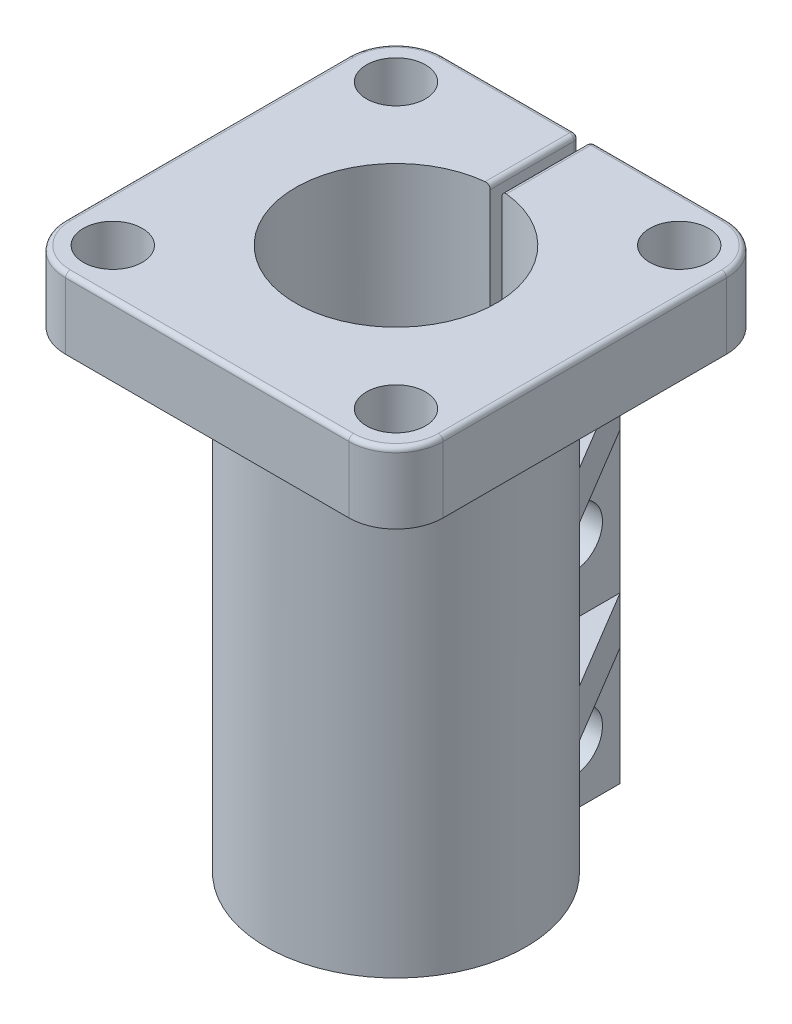
SolidWorks part; units mm, degrees
ref_plane "前视基准面" through (0, 0, 0) normal (0, 0, 1) x (1, 0, 0)
ref_plane "上视基准面" through (0, 0, 0) normal (0, 1, 0) x (1, 0, 0)
ref_plane "右视基准面" through (0, 0, 0) normal (1, 0, 0) x (0, 0, -1)
sketch "草图1" plane through (0, 0, 0) normal (0, 1, 0) x (1, 0, 0)
  line L0 (0, 0) -> (0, 9.0799) construction
  line L1 (-0.25, 8) -> (-0.25, 4.2426)
  line L2 (-0.25, 8) -> (-1.5, 8)
  line L3 (-1.5, 8) -> (-1.5, 5.2915)
  line L4 (1.5, 8) -> (1.5, 5.2915)
  line L5 (0.25, 8) -> (1.5, 8)
  line L6 (0.25, 8) -> (0.25, 4.2426)
  arc A0 (-0.25, 4.2426) -> (0.25, 4.2426) centre (0, 0) ccw
  arc A1 (-1.5, 5.2915) -> (1.5, 5.2915) centre (0, 0) ccw
  dimension "D1" = 8.5
  dimension "D2" = 11
  dimension "D3" = 1.25
  dimension "D4" = 0.25
  dimension "D5" = 8
extrude "凸台-拉伸1" add sketch "草图1" along normal blind 20
sketch "草图2" plane through (0, 20, 0) normal (0, 1, 0) x (1, 0, 0)
  line L0 (0, 0) -> (0, 13.3346) construction
  line L1 (-8, 8) -> (8, 8)
  line L2 (-8, 8) -> (-8, -8)
  line L3 (-8, -8) -> (8, -8)
  line L4 (8, 8) -> (8, -8)
  line L5 (0, 0) -> (13.1784, 0) construction
  dimension "D1" = 16
  dimension "D2" = 16
extrude "凸台-拉伸2" add sketch "草图2" along normal blind 3
sketch "草图3" plane through (0, 0, 0) normal (0, -1, 0) x (1, 0, 0)
  line L2 (0.25, -8) -> (0.25, -4.2426) construction
  line L5 (-0.25, -4.2426) -> (-0.25, -8) construction
  line L6 (-0.25, -8) -> (0.25, -8)
  line L8 (0.25, -8) -> (0.25, -4.2426)
  line L11 (-0.25, -4.2426) -> (-0.25, -8)
  arc A0 (0.25, -4.2426) -> (-0.25, -4.2426) centre (0, 0) ccw construction
  arc A2 (0.25, -4.2426) -> (-0.25, -4.2426) centre (0, 0) ccw
extrude "切除-拉伸1" cut sketch "草图3" against normal through all
sketch "草图4" plane through (0, 0, 0) normal (0, 0, 1) x (1, 0, 0)
  line L0 (-8, 20) -> (-5.5, 17.5)
  line L1 (-5.5, 20) -> (-5.5, 0) construction
rib "筋1" sketch "草图4" sketch "草图4" thickness 2 extrusion direction parallel to sketch draft on no parameters "D1"=2
pattern_circular "阵列(圆周)1" count 4 over 360 about axis through (0, 0, 0) along (0, 1, 0) skipping 3 of "筋1"
ref_plane "基准面1" through (0, 5, 0) normal (0, 1, 0) x (1, 0, 0)
sketch "草图6" plane through (0, 5, 0) normal (0, 1, 0) x (1, 0, 0)
  line L0 (-1.5, 8) -> (-4.0664, 3.7033)
  line L1 (-1.5, 8) -> (-1.5, 5.2915) construction
  line L2 (-1.5, 8) -> (-1.5, 5.2915)
  arc A0 (-1.5, 5.2915) -> (-5.4083, 1) centre (0, 0) ccw construction
  arc A1 (-1.5, 5.2915) -> (-4.0664, 3.7033) centre (0, 0) ccw
extrude "凸台-拉伸3" add sketch "草图6" along normal blind 2
pattern_linear "阵列(线性)1" count 2 spacing 8 along (0, 1, 0) of "凸台-拉伸3"
mirror "镜向1" about plane through (0, 0, 0) normal (1, 0, 0) of "凸台-拉伸3", "阵列(线性)1"
fillet "圆角1" radius 2 4 edges at (8, 21.5, -8) (8, 21.5, 8) (-8, 21.5, 8) (-8, 21.5, -8)
fillet "圆角2" radius 0.2 2 edges at (0.25, 11.5, -8) (-0.25, 11.5, -8)
fillet "圆角4" radius 0.2 13 edges at (0.3086, 23, -7.9414) (3.225, 23, -8) (7.4142, 23, -7.4142) (8, 23, 0) (7.4142, 23, 7.4142) (0, 23, 8) (-7.4142, 23, 7.4142) (-8, 23, 0) (-7.4142, 23, -7.4142) (-3.225, 23, -8) (-0.3086, 23, -7.9414) (0.25, 23, -6.0213) (-0.25, 23, -6.0213)
hole_wizard "M3 螺纹孔的螺纹孔钻头1" positions "草图7" profile "草图8" hole size "M3" standard "GB" end condition up to next
sketch "草图7" plane through (0, 20, 0) normal (0, -1, 0) x (-1, 0, 0)
  line L0 (0, 0) -> (0, 14.1408) construction
  line L2 (0, 0) -> (-17.2024, 0) construction
  arc A0 (7.8, 6) -> (6, 7.8) centre (6, 6) ccw construction
  point P0 (6, 6)
  point P2 (6, -6)
  point P4 (-6, 6)
  point P6 (-6, -6)
sketch "草图8" plane through (-6, 20, -6) normal (1, 0, 0) x (0, 0, -1)
  line L0 (0, 0) -> (0, 3)
  line L1 (0, 3) -> (1.25, 3)
  line L2 (1.25, 3) -> (1.25, 0)
  line L5 (1.25, 0) -> (0, 0)
  line L11 (0, -6.35) -> (0, 107.95) construction
  dimension "通孔孔直径" = 2.5
  dimension "通孔孔深度" = 3
sketch "草图11" plane through (-1.5, 0, 0) normal (-1, 0, 0) x (0, 0, 1)
  line L0 (-9.7616, 17.5) -> (-3.8678, 17.5) construction
  line L1 (-11.8183, 10) -> (-3.1618, 10) construction
  line L2 (-11.3579, 2.5) -> (-3.8678, 2.5) construction
  line L3 (-8, 0) -> (-5.2915, 0) construction
  line L7 (-5.2915, 7) -> (-8, 7) construction
  line L9 (-5.2915, 15) -> (-8, 15) construction
  line L11 (-8, 20) -> (-8, 15) construction
  circle A0 centre (-6, 17.5) radius 1.25
  circle A1 centre (-6, 10) radius 1.25
  circle A2 centre (-6, 2.5) radius 1.25
  dimension "D1" = 2.5
  dimension "D2" = 2.5
  dimension "D3" = 3
  dimension "D4" = 2.5
  dimension "D5" = 2
extrude "切除-拉伸2" cut sketch "草图11" against normal through all and the other way through all
sketch "草图12" plane through (-1.5, 0, 0) normal (-1, 0, 0) x (0, 0, 1)
  circle A0 centre (-6, 17.5) radius 1.75
  circle A1 centre (-6, 10) radius 1.75
  circle A2 centre (-6, 2.5) radius 1.75
  dimension "D1" = 3.5
extrude "切除-拉伸3" cut sketch "草图12" along normal blind 2
sketch "草图13" plane through (1.5, 0, 0) normal (1, 0, 0) x (0, 0, -1)
  line L1 (6, 19.5207) -> (4.25, 18.5104)
  line L2 (4.25, 18.5104) -> (4.25, 16.4896)
  line L3 (4.25, 16.4896) -> (6, 15.4793)
  line L4 (6, 15.4793) -> (7.75, 16.4896)
  line L5 (7.75, 16.4896) -> (7.75, 18.5104)
  line L6 (7.75, 18.5104) -> (6, 19.5207)
  line L7 (6, 12.0207) -> (4.25, 11.0104)
  line L8 (4.25, 11.0104) -> (4.25, 8.9896)
  line L9 (4.25, 8.9896) -> (6, 7.9793)
  line L10 (6, 7.9793) -> (7.75, 8.9896)
  line L11 (7.75, 8.9896) -> (7.75, 11.0104)
  line L12 (7.75, 11.0104) -> (6, 12.0207)
  line L13 (6, 4.5207) -> (4.25, 3.5104)
  line L14 (4.25, 3.5104) -> (4.25, 1.4896)
  line L15 (4.25, 1.4896) -> (6, 0.4793)
  line L16 (6, 0.4793) -> (7.75, 1.4896)
  line L17 (7.75, 1.4896) -> (7.75, 3.5104)
  line L18 (7.75, 3.5104) -> (6, 4.5207)
  circle A0 centre (6, 17.5) radius 1.75 construction
  circle A1 centre (6, 10) radius 1.75 construction
  circle A2 centre (6, 2.5) radius 1.75 construction
  dimension "D1" = 3.5
extrude "切除-拉伸4" cut sketch "草图13" along normal blind 2
sketch "草图16" plane through (0, 0, 8) normal (0, 0, 1) x (1, 0, 0)
  line L0 (0, 0) -> (0, 21.0314) construction
  line L1 (-3.8, 19) -> (-1.7, 19)
  line L2 (-4, 18.8) -> (-4, 17.7)
  line L3 (-3.8, 17.5) -> (-1.7, 17.5)
  line L4 (-1.5, 18.8) -> (-1.5, 17.7)
  line L5 (-5.5, 0) -> (5.5, 0) construction
  line L6 (-6, 20) -> (-1, 20) construction
  line L7 (1.5, 18.8) -> (1.5, 17.7)
  line L8 (3.8, 17.5) -> (1.7, 17.5)
  line L9 (4, 18.8) -> (4, 17.7)
  line L10 (3.8, 19) -> (1.7, 19)
  arc A0 (4, 18.8) -> (3.8, 19) centre (3.8, 18.8) ccw
  arc A1 (3.8, 17.5) -> (4, 17.7) centre (3.8, 17.7) ccw
  arc A2 (1.5, 17.7) -> (1.7, 17.5) centre (1.7, 17.7) ccw
  arc A3 (1.5, 18.8) -> (1.7, 19) centre (1.7, 18.8) cw
  arc A4 (-1.7, 19) -> (-1.5, 18.8) centre (-1.7, 18.8) cw
  arc A5 (-4, 17.7) -> (-3.8, 17.5) centre (-3.8, 17.7) ccw
  arc A6 (-1.7, 17.5) -> (-1.5, 17.7) centre (-1.7, 17.7) ccw
  arc A7 (-3.8, 19) -> (-4, 18.8) centre (-3.8, 18.8) ccw
  point P16 (4, 19)
  point P19 (4, 17.5)
  point P22 (1.5, 17.5)
  point P25 (1.5, 19)
  point P28 (-1.5, 19)
  point P31 (-4, 17.5)
  point P34 (-1.5, 17.5)
  point P37 (-4, 19)
  dimension "D5" = 0.2
  dimension "D1" = 2.5
  dimension "D2" = 1.5
  dimension "D3" = 1
  dimension "D4" = 1.5
extrude "切除-拉伸5" cut sketch "草图16" against normal blind 8
